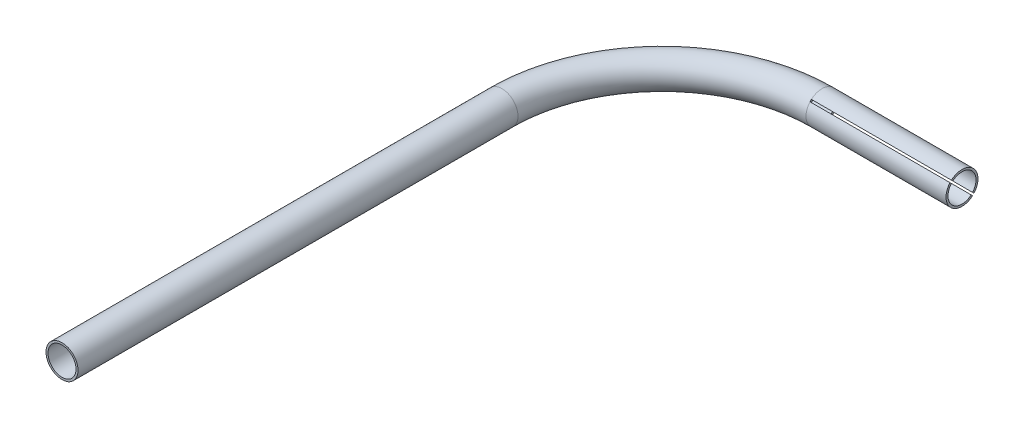
SolidWorks part; units mm, degrees
ref_plane "Спереди" through (0, 0, 0) normal (0, 0, 1) x (1, 0, 0)
ref_plane "Сверху" through (0, 0, 0) normal (0, 1, 0) x (1, 0, 0)
ref_plane "Справа" through (0, 0, 0) normal (1, 0, 0) x (0, 0, -1)
sketch "Эскиз1" plane through (0, 0, 0) normal (0, 1, 0) x (1, 0, 0)
  line L0 (-150, -300) -> (-150, -80)
  line L1 (0, 0) -> (-70, 0)
  line L2 (0, 0) -> (0, -87.0881) construction
  arc A0 (-150, -80) -> (-70, 0) centre (-70, -80) cw
  point P8 (0, 0)
  point P10 (0, 0)
  dimension "D1" = 80
  dimension "D2" = 150
  dimension "D3" = 300
sketch "Эскиз2" plane through (0, 0, 0) normal (1, 0, 0) x (0, 0, -1)
  circle A0 centre (0, 0) radius 8
  circle A1 centre (0, 0) radius 7
  dimension "D1" = 16
  dimension "D2" = 1
sweep "По траектории1" add profiles "Эскиз2" path "Эскиз1"
sketch "Эскиз3" plane through (0, 0, 0) normal (1, 0, 0) x (0, 0, -1)
  line L0 (0, 0) -> (-5.6569, 5.6569) construction
  line L1 (0, 0) -> (4.027, 0) construction
  line L2 (5.3033, -6.0104) -> (-6.0104, 5.3033)
  line L3 (5.3033, -6.0104) -> (6.0104, -5.3033)
  line L4 (-6.0104, 5.3033) -> (-5.3033, 6.0104)
  line L5 (6.0104, -5.3033) -> (-5.3033, 6.0104)
  line L6 (5.3033, -6.0104) -> (-5.3033, 6.0104) construction
  line L7 (-6.0104, 5.3033) -> (6.0104, -5.3033) construction
  circle A0 centre (0, 0) radius 8 construction
  dimension "D1" = 135
  dimension "D2" = 1
extrude "Вырез-Вытянуть1" cut sketch "Эскиз3" against normal blind 70
